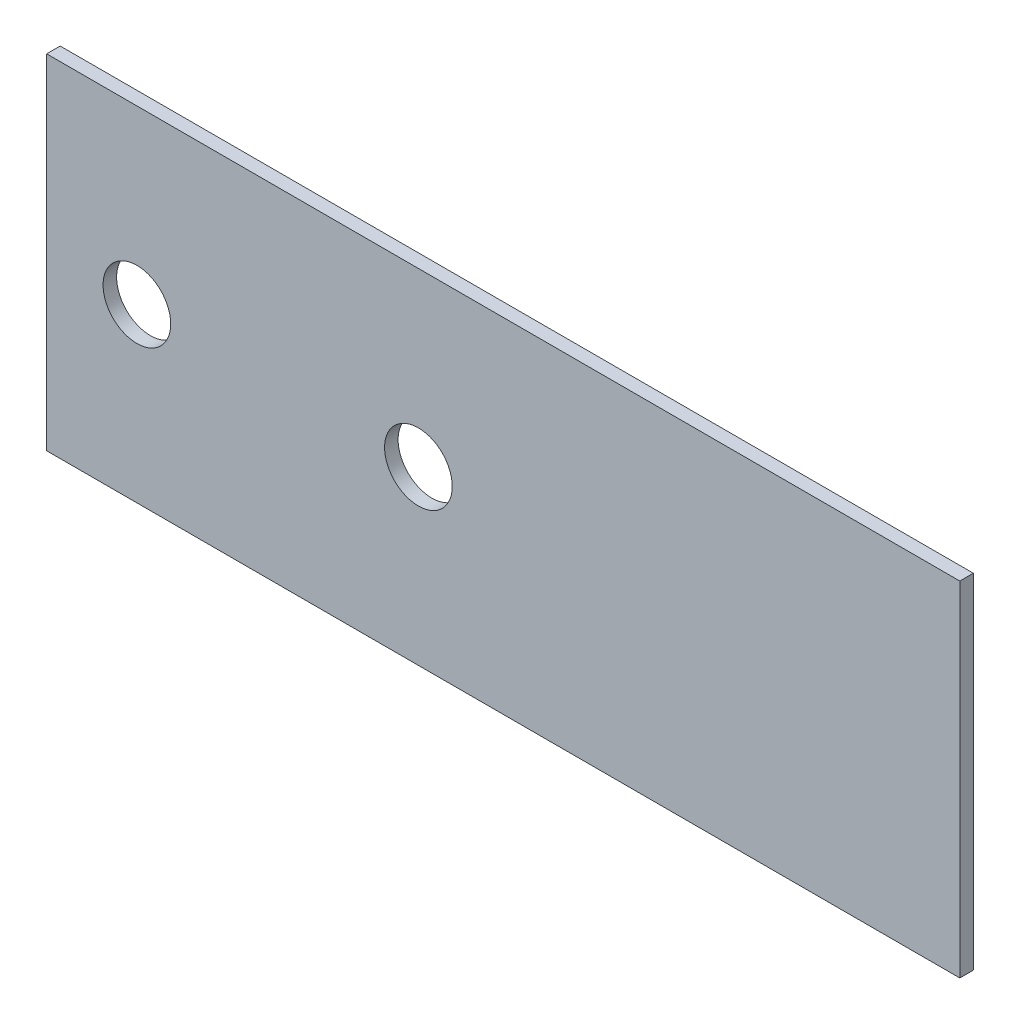
SolidWorks part; units mm, degrees
ref_plane "Front Plane" through (0, 0, 0) normal (0, 0, 1) x (1, 0, 0)
ref_plane "Top Plane" through (0, 0, 0) normal (0, 1, 0) x (1, 0, 0)
ref_plane "Right Plane" through (0, 0, 0) normal (1, 0, 0) x (0, 0, -1)
sketch "Sketch1" plane through (0, 0, 0) normal (0, 0, 1) x (1, 0, 0)
  line L1 (-101.2, 38.1) -> (101.2, 38.1)
  line L2 (-101.2, 38.1) -> (-101.2, -38.1)
  line L3 (-101.2, -38.1) -> (101.2, -38.1)
  line L4 (101.2, 38.1) -> (101.2, -38.1)
  line L5 (-101.2, 38.1) -> (101.2, -38.1) construction
  line L6 (-101.2, -38.1) -> (101.2, 38.1) construction
  point P0 (0, 0)
  dimension "D1" = 202.4
  dimension "D2" = 76.2
extrude "Boss-Extrude1" add sketch "Sketch1" along normal blind 3
sketch "Sketch2" plane through (0, 0, 3) normal (0, 0, 1) x (1, 0, 0)
  line L0 (-101.2, 38.1) -> (-101.2, -38.1) construction
  circle A0 centre (-81.2, 0) radius 7.5
  dimension "D1" = 15
  dimension "D2" = 20
extrude "Cut-Extrude1" cut sketch "Sketch2" against normal through all
sketch "Sketch3" plane through (0, 0, 3) normal (0, 0, 1) x (1, 0, 0)
  line L0 (101.2, -38.1) -> (101.2, 38.1) construction
  circle A0 centre (-18.8, 0) radius 7.5
  dimension "D1" = 15
  dimension "D2" = 120
extrude "Cut-Extrude2" cut sketch "Sketch3" against normal through all and the other way through all
